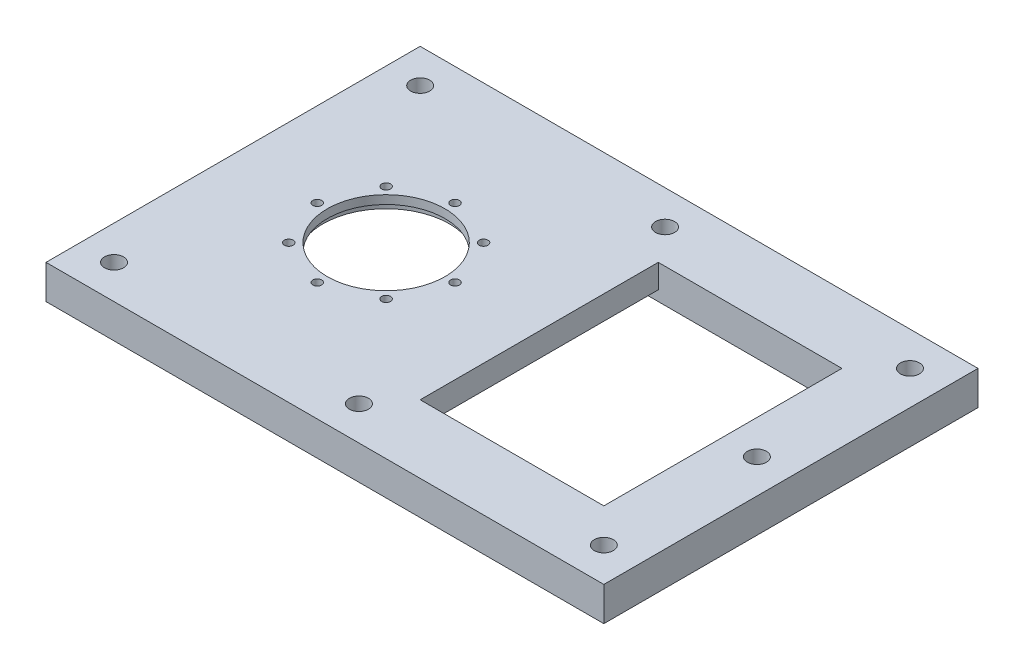
SolidWorks part; units mm, degrees
ref_plane "Front Plane" through (0, 0, 0) normal (0, 0, 1) x (1, 0, 0)
ref_plane "Top Plane" through (0, 0, 0) normal (0, 1, 0) x (1, 0, 0)
ref_plane "Right Plane" through (0, 0, 0) normal (1, 0, 0) x (0, 0, -1)
sketch "Sketch1" plane through (0, 0, 0) normal (0, 1, 0) x (1, 0, 0)
  circle A0 centre (0, 0) radius 17.3
  circle A1 centre (0, 0) radius 35
  dimension "D1" = 70
  dimension "D2" = 34.6
extrude "Boss-Extrude1" add sketch "Sketch1" along normal blind 2.5 contours A0 | A1
sketch "Sketch3" plane through (0, 0, 0) normal (0, -1, 0) x (1, 0, 0)
  circle A0 centre (0, 0) radius 18.6
  circle A3 centre (0, 0) radius 35 construction
  circle A4 centre (0, 0) radius 35
  dimension "D1" = 37.2
extrude "Boss-Extrude2" add sketch "Sketch3" along normal blind 2 contours A0 | A4
sketch "Sketch4" plane through (0, -2, 0) normal (0, -1, 0) x (1, 0, 0)
  circle A0 centre (0, 0) radius 22.3
  circle A2 centre (0, 0) radius 35 construction
  circle A3 centre (0, 0) radius 35
extrude "Boss-Extrude3" add sketch "Sketch4" along normal blind 2
sketch "Sketch6" plane through (0, 2.5, 0) normal (0, 1, 0) x (1, 0, 0)
  circle A0 centre (0, 0) radius 20.25 construction
  circle A1 centre (0, 20.25) radius 1.3
  circle A2 centre (14.3189, 14.3189) radius 1.3
  circle A3 centre (20.25, 0) radius 1.3
  circle A4 centre (14.3189, -14.3189) radius 1.3
  circle A5 centre (0, -20.25) radius 1.3
  circle A6 centre (-14.3189, -14.3189) radius 1.3
  circle A7 centre (-20.25, 0) radius 1.3
  circle A8 centre (-14.3189, 14.3189) radius 1.3
  point P22 (0, 0)
  dimension "D1" = 40.5
  dimension "D2" = 2.6
  dimension "D3" = 8
extrude "Cut-Extrude1" cut sketch "Sketch6" against normal up to next contours A8 | A7 | A6 | A5 | A4 | A3 | A2 | A1
sketch "Sketch7" plane through (0, 2.5, 0) normal (0, 1, 0) x (1, 0, 0)
  line L0 (45, -35) -> (99, -35)
  line L1 (-45, 55) -> (99, 55)
  line L2 (-45, 55) -> (-45, 35)
  line L3 (-45, 35) -> (99, 35) construction
  line L4 (99, 55) -> (99, 35) construction
  line L5 (99, 55) -> (119, 55)
  line L6 (99, 55) -> (99, -55) construction
  line L7 (99, -55) -> (119, -55)
  line L8 (119, 55) -> (119, -55)
  line L9 (-45, 35) -> (-35, 35) construction
  line L10 (-45, 35) -> (-45, -55)
  line L11 (-45, -55) -> (-35, -55)
  line L12 (-35, 35) -> (-35, -55) construction
  line L13 (-35, -55) -> (99, -55)
  line L14 (-35, -55) -> (-35, -35)
  line L15 (-35, -35) -> (99, -35) construction
  line L16 (99, -55) -> (99, -35) construction
  line L17 (35, 35) -> (45, 35) construction
  line L18 (35, 35) -> (35, -35) construction
  line L19 (35, -35) -> (45, -35) construction
  line L20 (45, 35) -> (45, -35)
  line L21 (99, -35) -> (99, 35)
  line L22 (99, 35) -> (45, 35)
  circle A0 centre (0, 0) radius 35
  circle A2 centre (0, 0) radius 35 construction
  dimension "D2" = 10
  dimension "D1" = 20
  dimension "D3" = 64
  dimension "D4" = 20
  dimension "D5" = 20
  dimension "D6" = 10
extrude "Boss-Extrude6" add sketch "Sketch7" against normal blind 10
sketch "Sketch8" plane through (0, -7.5, 0) normal (0, -1, 0) x (1, 0, 0)
  line L1 (45, 35) -> (38, 35)
  line L2 (45, 35) -> (45, -35)
  line L3 (45, -35) -> (38, -35)
  line L4 (38, 35) -> (38, -35)
  line L5 (99, 35) -> (106, 35)
  line L6 (99, 35) -> (99, -35)
  line L7 (99, -35) -> (106, -35)
  line L8 (106, 35) -> (106, -35)
  line M12 (99, 35) -> (99, -35)
  dimension "D1" = 7
extrude "Cut-Extrude3" cut sketch "Sketch8" against normal blind 3 contours L8 L5 L7 M12 | L1 L4 L3 L2
sketch "Sketch10" plane through (0, 2.5, 0) normal (0, 1, 0) x (1, 0, 0)
  line L2 (-45, 45) -> (119, 45)
  line L3 (-45, 45) -> (119, 45) construction
  line L5 (-35, 55) -> (-35, -55)
  line L6 (-35, 55) -> (-35, -55) construction
  line L8 (-45, -45) -> (119, -45)
  line L9 (-45, -45) -> (119, -45) construction
  line L11 (109, 55) -> (109, -55)
  line L12 (109, 55) -> (109, -55) construction
  circle A0 centre (37, 45) radius 2.8
  circle A1 centre (-35, 45) radius 2.8
  circle A2 centre (-35, -45) radius 2.8
  circle A3 centre (37, -45) radius 2.8
  circle A4 centre (109, 45) radius 2.8
  circle A5 centre (109, -45) radius 2.8
  circle A6 centre (109, 0) radius 2.8
  dimension "D5" = 5.6
  dimension "D6" = 5.6
  dimension "D7" = 5.6
  dimension "D8" = 5.6
  dimension "D9" = 5.6
  dimension "D10" = 5.6
  dimension "D1" = 10
  dimension "D2" = 10
  dimension "D3" = 10
  dimension "D4" = 10
extrude "Cut-Extrude4" cut sketch "Sketch10" against normal up to next
